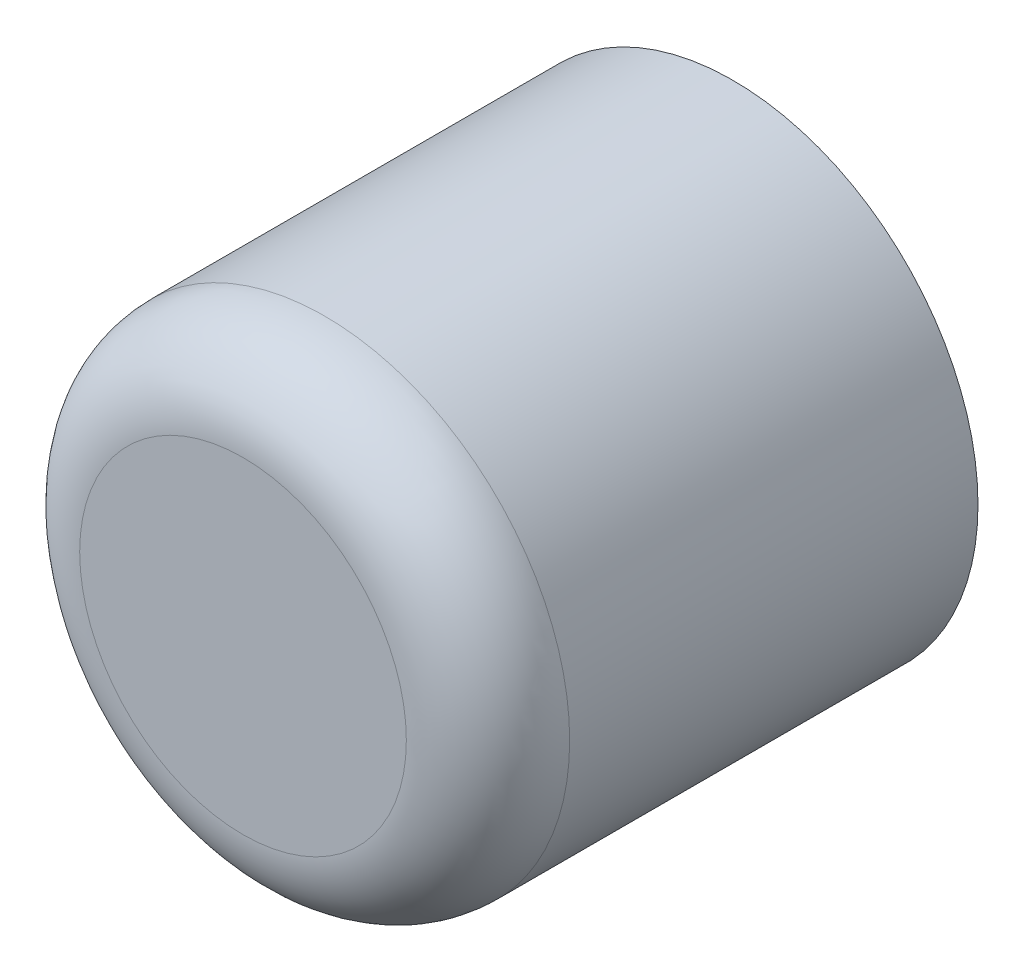
SolidWorks part; units mm, degrees
ref_plane "前视基准面" through (0, 0, 0) normal (0, 0, 1) x (1, 0, 0)
ref_plane "上视基准面" through (0, 0, 0) normal (0, 1, 0) x (1, 0, 0)
ref_plane "右视基准面" through (0, 0, 0) normal (1, 0, 0) x (0, 0, -1)
sketch "草图1" plane through (0, 0, 0) normal (0, 0, 1) x (1, 0, 0)
  circle A0 centre (0, 0) radius 3
  dimension "D1" = 6
extrude "凸台-拉伸1" add sketch "草图1" along normal blind 6
fillet "圆角1" radius 1 1 edges at (3, 0, 6)
sketch "草图2" plane through (0, 0, 0) normal (0, 0, -1) x (-1, 0, 0)
  line L1 (1.7321, 0) -> (0.866, 1.5)
  line L2 (0.866, 1.5) -> (-0.866, 1.5)
  line L3 (-0.866, 1.5) -> (-1.7321, 0)
  line L4 (-1.7321, 0) -> (-0.866, -1.5)
  line L5 (-0.866, -1.5) -> (0.866, -1.5)
  line L6 (0.866, -1.5) -> (1.7321, 0)
  circle A0 centre (0, 0) radius 1.5 construction
extrude "切除-拉伸1" cut sketch "草图2" against normal blind 1.5
